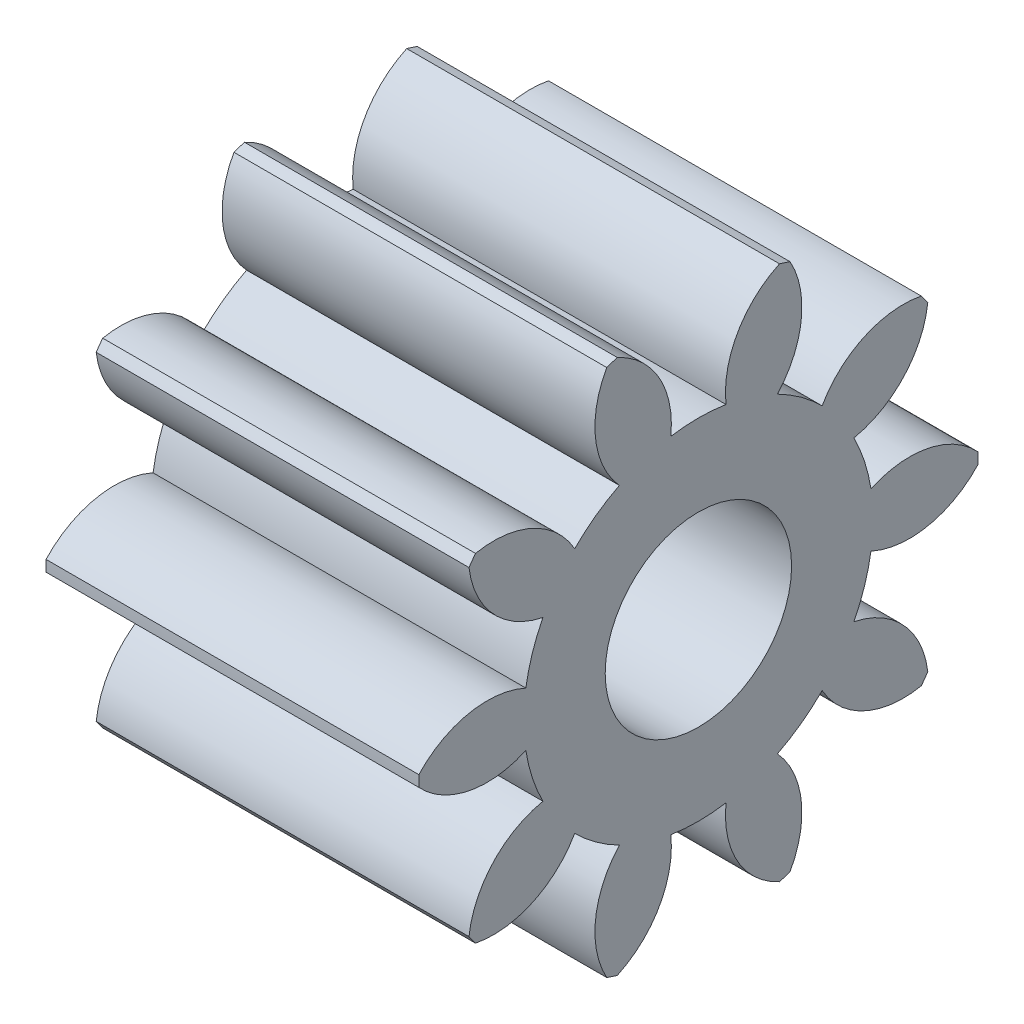
SolidWorks part; units mm, degrees
ref_plane "Plane1" through (0, 0, 0) normal (0, 0, 1) x (1, 0, 0)
ref_plane "Plane2" through (0, 0, 0) normal (0, 1, 0) x (1, 0, 0)
ref_plane "Plane3" through (0, 0, 0) normal (1, 0, 0) x (0, 0, -1)
sketch "HoldingSke" plane through (0, 0, 0) normal (0, 1, 0) x (1, 0, 0)
  line L0 (0, 0) -> (1.9696, -0.3473)
  line L1 (-15, 0) -> (100, 0) construction
  line L2 (0, 0) -> (-2.1039, 2.3779)
  line L3 (0, 0) -> (-11.863, 4.5341)
  line L4 (0, 0) -> (8.5048, 1.4996)
  line L5 (0, 0) -> (-46.8476, -17.4728)
  line L6 (0, 0) -> (-2.9014, -1.9576)
  line L7 (-2.1039, 2.3779) -> (8.6586, 51.2059)
  line L8 (-76.2, 54.61) -> (-75.9, 54.61)
  line L9 (-71.009, 38.7566) -> (-53.1078, 45.2721)
  line L10 (-76.2, 71.12) -> (104.1128, 71.12)
  line L11 (0, 0) -> (-3.5, 0)
  line L12 (-76.2, 101.6) -> (-76.181, 101.6)
  line L13 (24.9733, 27.94) -> (52.9518, 28.4284)
  line L14 (24.9733, 27.94) -> (24.9743, 27.94)
  line L15 (24.9733, 27.94) -> (100.4006, 29.5858)
  line L16 (-63.627, -0.5) -> (-12.827, -0.5)
  circle A0 centre (0, 0) radius 1
  circle A1 centre (0, 0) radius 1.874
  circle A2 centre (0, 0) radius 37.5
  circle A3 centre (0, 0) radius 1
  dimension "MHD" = 3.748
  dimension "Hub_dia" = 75
  dimension "Bore" = 2
  dimension "MBD" = 2
  dimension "Num_teeth" = 10
  dimension "Pitch" = 2
  dimension "Overall_len" = 50
  dimension "Show_teeth" = 10
  dimension "Thickness" = 3.5
  dimension "OAL" = 50.0001
  dimension "T_dim" = 0.3
  dimension "Ap" = 20
  dimension "H" = 19.05
  dimension "Pitch_radius" = 180.3128
  dimension "Width" = 3.5
  dimension "Backlash" = 0.019
  dimension "Addendum_fac" = 1
  dimension "Dedendum_fac" = 1.25
  dimension "Clearance_fac" = 0.25
  dimension "Dedendum_add" = 0.001
  dimension "Module" = 0.5
sketch "BasProSke" plane through (0, 0, 0) normal (0, 1, 0) x (1, 0, 0)
  line L0 (-10, 0) -> (60, 0) construction
  line L1 (0, 0) -> (0, 3)
  line L2 (0, 0) -> (4, 0)
  line L3 (4, 0) -> (4, 3)
  line L4 (4, 3) -> (0, 3)
  dimension "Thickness" = 4
  dimension "Diameter" = 6
revolve "Base-Revolve" add sketch "BasProSke" angle 360 about L0
sketch "TooCutSke" plane through (0, 0, 0) normal (1, 0, 0) x (0, 0, -1)
  line L1 (0, 0) -> (0, 107) construction
  line L2 (0, 0) -> (-0.4243, 2.4637) construction
  line L3 (0, 0) -> (-1.5292, 4.7063) construction
  line L4 (-0.4243, 2.4637) -> (-0.7646, 2.3532) construction
  arc A0 (0.2964, 1.8504) -> (-0.2964, 1.8504) centre (0, 0) ccw
  arc A1 (0.9059, 2.8866) -> (-0.9059, 2.8866) centre (0, 0) ccw
  circle A2 centre (0, 0) radius 2.5 construction
  circle A3 centre (0, 0) radius 2.3492 construction
  arc A4 (-0.2964, 1.8504) -> (-0.9059, 2.8866) centre (-1.2901, 1.9633) ccw
  arc A5 (0.9059, 2.8866) -> (0.2964, 1.8504) centre (1.2901, 1.9633) ccw
  dimension "Root_dia" = 3.748
  dimension "Overcut_dia" = 6.0508
  dimension "Pitch_dia" = 5
  dimension "Base_dia" = 4.6985
  dimension "Flank_rad" = 1
  dimension "Half_ang" = 18
  dimension "Half_CT" = 0.3578
extrude "ToothCut" cut sketch "TooCutSke" along normal through all
fillet "Breaks" [suppressed] radius 0.01
fillet "RootFillets" [suppressed] radius 0.126
pattern_circular "TeethCuts" count 10 every 36 about axis through (-10, 0, 0) along (1, 0, 0) of "ToothCut", "RootFillets", "Breaks"
sketch "HubNeaOneSke" plane through (0, 0, 0) normal (-1, 0, 0) x (0, 0, 1)
  circle A0 centre (0, 0) radius 1.874
  dimension "Diameter" = 3.748
extrude "HubNearOne" [suppressed] add sketch "HubNeaOneSke" along normal blind 46.0001
sketch "HubNeaBotSke" plane through (0, 0, 0) normal (-1, 0, 0) x (0, 0, 1)
  circle A0 centre (0, 0) radius 1.874
  dimension "Diameter" = 3.748
extrude "HubNearBoth" [suppressed] add sketch "HubNeaBotSke" along normal blind 23
ref_plane "FarPln" through (4, 0, 0) normal (1, 0, 0) x (0, 0, -1)
sketch "HubFarSke" plane through (4, 0, 0) normal (1, 0, 0) x (0, 0, -1)
  circle A0 centre (0, 0) radius 1.874
  dimension "Diameter" = 3.748
extrude "HubFar" [suppressed] add sketch "HubFarSke" along normal blind 23
sketch "BorSke" plane through (0, 0, 0) normal (1, 0, 0) x (0, 0, -1)
  circle A0 centre (0, 0) radius 1
  dimension "Diameter" = 2
extrude "Bore" cut sketch "BorSke" along normal mid plane 100.0001
sketch "KeySke" plane through (0, 0, 0) normal (1, 0, 0) x (0, 0, -1)
  line L0 (-0.4, 0) -> (-0.4, 1.3)
  line L1 (-0.4, 1.3) -> (0.4, 1.3)
  line L2 (0.4, 1.3) -> (0.4, 0)
  line L3 (0, 0) -> (0, 34) construction
  line L4 (-0.4, 0) -> (0.4, 0)
  dimension "Offset" = 1.3
  dimension "Width" = 0.8
extrude "Keyway" [suppressed] cut sketch "KeySke" along normal mid plane 100.0001
pattern_circular "Keyway2" [suppressed] count 2 every 90 about axis through (-10, 0, 0) along (1, 0, 0)
equation "' \"Module@HoldingSke\" = 6.35"
equation "' \"Num_teeth@HoldingSke\" = 12"
equation "' \"Ap@HoldingSke\" =  20"
equation "' \"Ap@HoldingSke\" = 20"
equation "' \"Width@HoldingSke\" = 0.5 * 25.4"
equation "' \"Hub_dia@HoldingSke\"= 1 * 25.4"
equation "' \"Hub_dia@HoldingSke\" = 1 * 25.4"
equation "' \"Overall_len@HoldingSke\" = 1.0 * 25.4"
equation "' \"Bore@HoldingSke\" = 0.75 * 25.4"
equation "' \"T_dim@HoldingSke\" = 0.1 * 25.4"
equation "' \"Width@KeySke\" = 0.25 * 25.4"
equation "' \"Show_teeth@HoldingSke\" = 13"
equation "' \"Backlash@HoldingSke\" = 0.009 * 25.4"
equation "' \"Addendum_fac@HoldingSke\" = 1.0"
equation "' \"Dedendum_fac@HoldingSke\" = 1.25"
equation "' \"Dedendum_add@HoldingSke\" = 0.00005 * 25.4"
equation "' \"Clearance_fac@HoldingSke\" = 0.25"
equation "\"Pitch@HoldingSke\" = 1 / \"Module@HoldingSke\""
equation "\"Overcut_dia@TooCutSke\" = (\"Num_teeth@HoldingSke\" + 2 * \"Addendum_fac@HoldingSke\") / \"Pitch@HoldingSke\" + 0.002 * 25.4"
equation "\"Pitch_dia@TooCutSke\" = \"Num_teeth@HoldingSke\" / \"Pitch@HoldingSke\""
equation "\"Base_dia@TooCutSke\" = \"Num_teeth@HoldingSke\" / \"Pitch@HoldingSke\" * cos((\"Ap@HoldingSke\"  * 3.14159265 / 180))"
equation "\"Root_dia@TooCutSke\" = (\"Num_teeth@HoldingSke\" + 2) / \"Pitch@HoldingSke\" - 2 * (\"Addendum_fac@HoldingSke\" + \"Dedendum_fac@HoldingSke\") / \"Pitch@HoldingSke\" - \"Dedendum_add@HoldingSke\" * 2"
equation "\"Half_ang@TooCutSke\" = 180 / \"Num_teeth@HoldingSke\""
equation "\"Half_CT@TooCutSke\" = \"Num_teeth@HoldingSke\" / \"Pitch@HoldingSke\" * sin((3.14159265 / 2 / \"Num_teeth@HoldingSke\")) / 2 - 7 * \"Backlash@HoldingSke\" / 4"
equation "\"Flank_rad@TooCutSke\" = \"Num_teeth@HoldingSke\" / \"Pitch@HoldingSke\" / 5"
equation "\"Radius@RootFillets\" = \"Clearance_fac@HoldingSke\" / \"Pitch@HoldingSke\" + \"Dedendum_add@HoldingSke\""
equation "\"Break_rad@Breaks\" = 0.02 / \"Pitch@HoldingSke\""
equation "\"Thickness@HoldingSke\" = \"Width@HoldingSke\""
equation "\"OAL@HoldingSke\" = \"Thickness@HoldingSke\""
equation "\"MHD@HoldingSke\" = (\"Num_teeth@HoldingSke\" + 2) / \"Pitch@HoldingSke\" - 2 * (\"Addendum_fac@HoldingSke\" + \"Dedendum_fac@HoldingSke\")  / \"Pitch@HoldingSke\" - \"Dedendum_add@HoldingSke\" * 2"
equation "\"MBD@HoldingSke\" = (\"Num_teeth@HoldingSke\" + 2) / \"Pitch@HoldingSke\" - 2 * (\"Addendum_fac@HoldingSke\" + \"Dedendum_fac@HoldingSke\")  / \"Pitch@HoldingSke\" - \"Dedendum_add@HoldingSke\" * 2 - 0.002 * 25.4"
equation "\"MHD@HoldingSke\" = ((sgn( \"MHD@HoldingSke\" - \"Hub_dia@HoldingSke\" )-1)*( \"MHD@HoldingSke\" - \"Hub_dia@HoldingSke\" ))/-2+ \"Hub_dia@HoldingSke\""
equation "\"MBD@HoldingSke\" = ((sgn( \"MBD@HoldingSke\" - \"Bore@HoldingSke\" )-1)*( \"MBD@HoldingSke\" - \"Bore@HoldingSke\" ))/-2+ \"Bore@HoldingSke\""
equation "\"OAL@HoldingSke\" = ((sgn( \"OAL@HoldingSke\" - \"Overall_len@HoldingSke\" )+1)*( \"OAL@HoldingSke\" - \"Overall_len@HoldingSke\" ))/2 + \"Overall_len@HoldingSke\" + 0.000002 * 25.4"
equation "\"Num_teeth@TeethCuts\" = int( \"Show_teeth@HoldingSke\" ) + 1"
equation "\"Num_teeth@TeethCuts\" = ((sgn( \"Num_teeth@TeethCuts\" - \"Num_teeth@HoldingSke\" )-1)*( \"Num_teeth@TeethCuts\" - \"Num_teeth@HoldingSke\" ))/-2+ \"Num_teeth@HoldingSke\""
equation "\"Num_teeth@TeethCuts\" = ((sgn( \"Num_teeth@TeethCuts\" - 2.0)+1)*( \"Num_teeth@TeethCuts\" - 2.0))/2 +2.0"
equation "\"Angle@TeethCuts\" = 360.0 / \"Num_teeth@HoldingSke\""
equation "\"Diameter@BasProSke\" = (\"Num_teeth@HoldingSke\" + 2 * \"Addendum_fac@HoldingSke\") / \"Pitch@HoldingSke\""
equation "\"Thickness@BasProSke\"=\"Thickness@HoldingSke\"+0.5"
equation "' \"Fillet_rad@BasProSke\" =  \"Thickness@HoldingSke\" * 0.05"
equation "' \"Fillet_rad@BasProSke\" = \"Thickness@HoldingSke\" * 0.05"
equation "\"MHD@HoldingSke\" = ((sgn( \"MHD@HoldingSke\" - \"Root_dia@TooCutSke\" )-1)*( \"MHD@HoldingSke\" - \"Root_dia@TooCutSke\" ))/-2+ \"Root_dia@TooCutSke\""
equation "\"Diameter@HubNeaOneSke\" = \"MHD@HoldingSke\""
equation "\"Length@HubNearOne\" = \"OAL@HoldingSke\" - \"Thickness@BasProSke\""
equation "\"Diameter@HubNeaBotSke\" = \"MHD@HoldingSke\""
equation "\"Length@HubNearBoth\" = ( \"OAL@HoldingSke\" - \"Thickness@BasProSke\" ) / 2.0"
equation "\"Thickness@FarPln\" = \"Thickness@BasProSke\""
equation "\"Diameter@HubFarSke\" = \"MHD@HoldingSke\""
equation "\"Length@HubFar\" = ( \"OAL@HoldingSke\" - \"Thickness@BasProSke\" ) / 2.0"
equation "\"Diameter@BorSke\" = \"MBD@HoldingSke\""
equation "\"D1@Bore\" = \"OAL@HoldingSke\" * 2.0"
equation "\"D1@Keyway\" = \"OAL@HoldingSke\" * 2.0"
equation "\"Offset@KeySke\" = \"T_dim@HoldingSke\" + \"MBD@HoldingSke\" / 2.0"
